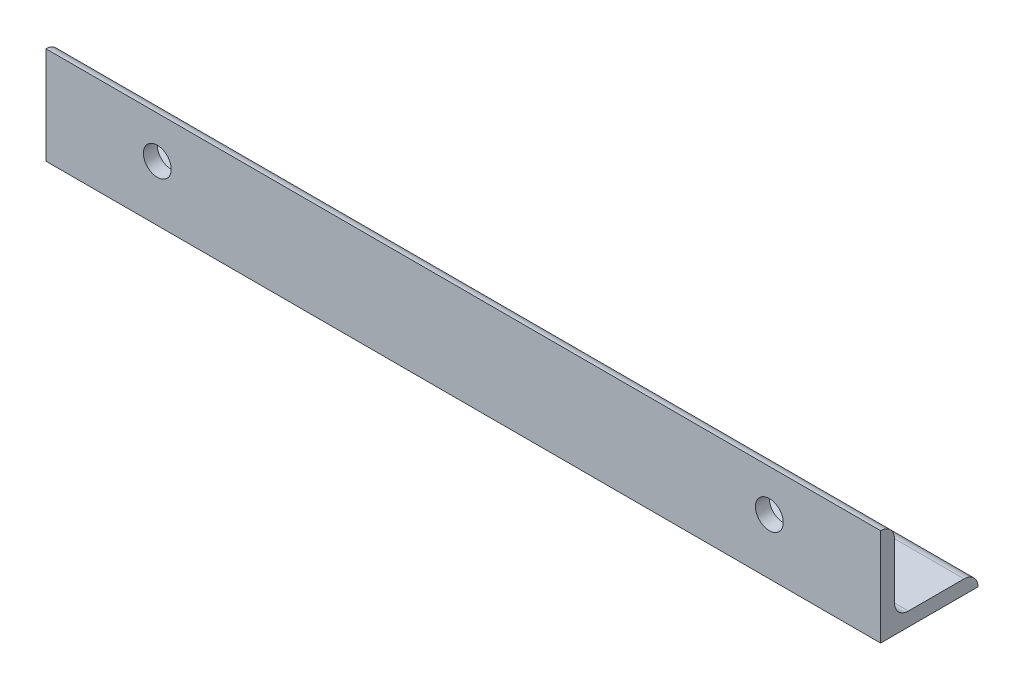
SolidWorks part; units mm, degrees
ref_plane "Płaszczyzna przednia" through (0, 0, 0) normal (0, 0, 1) x (1, 0, 0)
ref_plane "Płaszczyzna górna" through (0, 0, 0) normal (0, 1, 0) x (1, 0, 0)
ref_plane "Płaszczyzna prawa" through (0, 0, 0) normal (1, 0, 0) x (0, 0, -1)
sketch3d "Szkic 3D1"
  line L0 (0, 0, 0) -> (300, 0, 0)
  dimension "D1" = 300
other "Kątownik stalowy 35 X 35 X 5(1)"
ref_plane "Płaszczyzna1" through (0, 0, 0) normal (1, 0, 0) x (0, 0, -1)
sketch "Sketch1" plane through (0, 0, 0) normal (1, 0, 0) x (0, 0, -1)
  line L0 (0, 0) -> (0, 35)
  line L1 (0, 17.5) -> (5, 17.5) construction
  line L2 (5, 30) -> (5, 10)
  line L3 (10, 5) -> (30, 5)
  line L4 (17.5, 5) -> (17.5, 0) construction
  line L5 (35, 0) -> (0, 0)
  arc A0 (35, 0) -> (30, 5) centre (30, 0) ccw
  arc A1 (0, 35) -> (5, 30) centre (0, 30) cw
  arc A2 (10, 5) -> (5, 10) centre (10, 10) cw
  point P10 (17.5, 0)
  point P14 (0, 17.5)
  point P15 (5, 17.5)
  point P16 (17.5, 5)
  point P17 (5, 35)
  point P18 (35, 5)
  point P21 (0, 0)
  dimension "D2" = 5
  dimension "D3" = 35
  dimension "Radius_1" = 5
  dimension "D1" = 5
sketch "Szkic2" plane through (0, 0, -5) normal (0, 0, -1) x (-1, 0, 0)
  line L0 (-150, 69.0731) -> (-150, -74.3509) construction
  line L3 (-300, 35) -> (0, 35) construction
  circle A0 centre (-260, 20) radius 5
  circle A1 centre (-40, 20) radius 5
  point P6 (0, 0)
  point P13 (0, 0)
  dimension "D1" = 220
  dimension "D2" = 10
  dimension "D3" = 15
extrude "Wytnij-wyciągnięcie1" cut sketch "Szkic2" against normal through all
